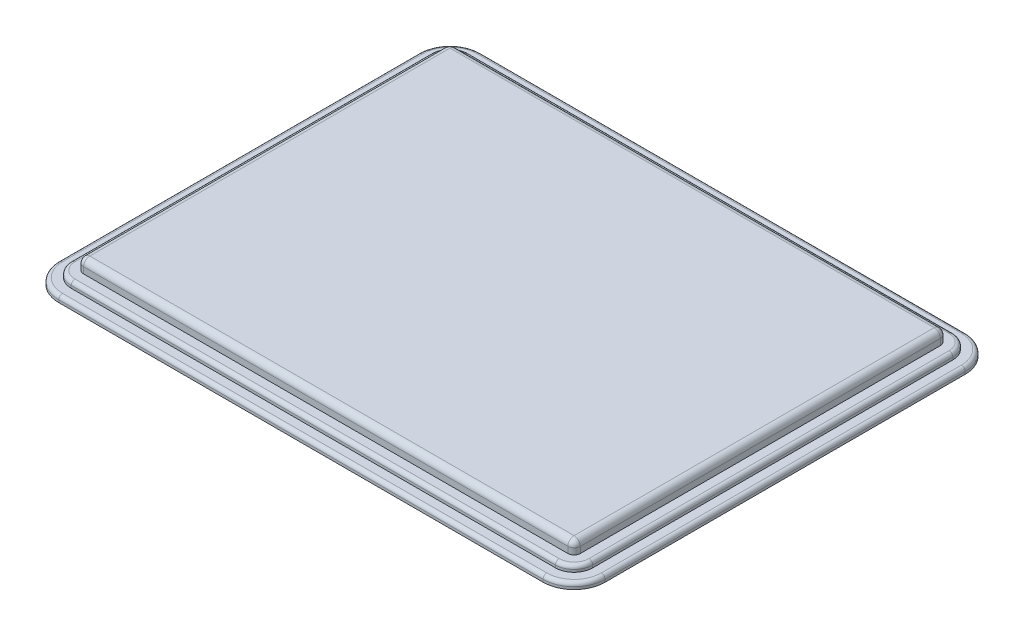
SolidWorks part; units mm, degrees
ref_plane "Front Plane" through (0, 0, 0) normal (0, 0, 1) x (1, 0, 0)
ref_plane "Top Plane" through (0, 0, 0) normal (0, 1, 0) x (1, 0, 0)
ref_plane "Right Plane" through (0, 0, 0) normal (1, 0, 0) x (0, 0, -1)
sketch "Sketch3" plane through (0, 0, 0) normal (0, 1, 0) x (1, 0, 0)
  line L1 (195, -150) -> (-195, -150)
  line L2 (200, -145) -> (200, 145)
  line L3 (195, 150) -> (-195, 150)
  line L4 (-200, -145) -> (-200, 145)
  line L5 (200, -150) -> (-200, 150) construction
  line L6 (200, 150) -> (-200, -150) construction
  arc A0 (-195, -150) -> (-200, -145) centre (-195, -145) cw
  arc A1 (200, 145) -> (195, 150) centre (195, 145) ccw
  arc A2 (195, -150) -> (200, -145) centre (195, -145) ccw
  arc A3 (-195, 150) -> (-200, 145) centre (-195, 145) ccw
  point P0 (0, 0)
  dimension "D3" = 5
  dimension "D1" = 400
  dimension "D2" = 300
extrude "Boss-Extrude1" add sketch "Sketch3" along normal blind 10
fillet "Fillet1" radius 5 8 edges at (-200, 10, 0) (-198.5355, 10, -148.5355) (0, 10, -150) (198.5355, 10, -148.5355) (200, 10, 0) (198.5355, 10, 148.5355) (0, 10, 150) (-198.5355, 10, 148.5355)
sketch "Sketch4" plane through (0, 0, 0) normal (0, -1, 0) x (1, 0, 0)
  line L0 (-210, 145) -> (-210, -145)
  line L1 (-195, -160) -> (195, -160)
  line L2 (210, -145) -> (210, 145)
  line L3 (195, 160) -> (-195, 160)
  line L4 (-200, 145) -> (-200, -145)
  line L5 (-195, -150) -> (195, -150)
  line L6 (200, -145) -> (200, 145)
  line L7 (195, 150) -> (-195, 150)
  line L8 (-200, 145) -> (-200, -145)
  line L9 (-195, -150) -> (195, -150)
  line L10 (200, -145) -> (200, 145)
  line L11 (195, 150) -> (-195, 150)
  arc A0 (-210, -145) -> (-195, -160) centre (-195, -145) ccw
  arc A1 (195, -160) -> (210, -145) centre (195, -145) ccw
  arc A2 (210, 145) -> (195, 160) centre (195, 145) ccw
  arc A3 (-195, 160) -> (-210, 145) centre (-195, 145) ccw
  arc A4 (-195, 150) -> (-200, 145) centre (-195, 145) ccw
  arc A5 (-200, -145) -> (-195, -150) centre (-195, -145) ccw
  arc A6 (195, -150) -> (200, -145) centre (195, -145) ccw
  arc A7 (200, 145) -> (195, 150) centre (195, 145) ccw
  arc A8 (-195, 150) -> (-200, 145) centre (-195, 145) ccw
  arc A9 (-200, -145) -> (-195, -150) centre (-195, -145) ccw
  arc A10 (195, -150) -> (200, -145) centre (195, -145) ccw
  arc A11 (200, 145) -> (195, 150) centre (195, 145) ccw
  arc M17 (-195, 150) -> (-200, 145) centre (-195, 145) ccw
  line M18 (-200, 145) -> (-200, -145)
  arc M19 (-200, -145) -> (-195, -150) centre (-195, -145) ccw
  line M20 (-195, -150) -> (195, -150)
  arc M21 (195, -150) -> (200, -145) centre (195, -145) ccw
  line M22 (200, -145) -> (200, 145)
  arc M23 (200, 145) -> (195, 150) centre (195, 145) ccw
  line M24 (195, 150) -> (-195, 150)
  dimension "D1" = 0
  dimension "D2" = 10
extrude "Boss-Extrude2" add sketch "Sketch4" along normal blind 5 separate body contours M24 M17 M18 M19 M20 M21 M22 M23 | L3 A3 L0 A0 L1 A1 L2 A2 M17 M24 M23 M22 M21 M20 M19 M18 | A8 L8 A9 L9 A10 L10 A11 L11
sketch "Sketch5" plane through (0, -5, 0) normal (0, -1, 0) x (1, 0, 0)
  line L0 (-220, 145) -> (-220, -145)
  line L1 (-195, -170) -> (195, -170)
  line L2 (220, -145) -> (220, 145)
  line L3 (195, 170) -> (-195, 170)
  line L4 (195, 160) -> (-195, 160)
  line L5 (-210, 145) -> (-210, -145)
  line L6 (-195, -160) -> (195, -160)
  line L7 (210, -145) -> (210, 145)
  line L8 (195, 160) -> (-195, 160)
  line L9 (-210, 145) -> (-210, -145)
  line L10 (-195, -160) -> (195, -160)
  line L11 (210, -145) -> (210, 145)
  arc A0 (-220, -145) -> (-195, -170) centre (-195, -145) ccw
  arc A1 (195, -170) -> (220, -145) centre (195, -145) ccw
  arc A2 (220, 145) -> (195, 170) centre (195, 145) ccw
  arc A3 (-195, 170) -> (-220, 145) centre (-195, 145) ccw
  arc A4 (-195, 160) -> (-210, 145) centre (-195, 145) ccw
  arc A5 (-210, -145) -> (-195, -160) centre (-195, -145) ccw
  arc A6 (195, -160) -> (210, -145) centre (195, -145) ccw
  arc A7 (210, 145) -> (195, 160) centre (195, 145) ccw
  arc A8 (-195, 160) -> (-210, 145) centre (-195, 145) ccw
  arc A9 (-210, -145) -> (-195, -160) centre (-195, -145) ccw
  arc A10 (195, -160) -> (210, -145) centre (195, -145) ccw
  arc A11 (210, 145) -> (195, 160) centre (195, 145) ccw
  line M17 (195, 160) -> (-195, 160)
  arc M18 (-195, 160) -> (-210, 145) centre (-195, 145) ccw
  line M19 (-210, 145) -> (-210, -145)
  arc M20 (-210, -145) -> (-195, -160) centre (-195, -145) ccw
  line M21 (-195, -160) -> (195, -160)
  arc M22 (195, -160) -> (210, -145) centre (195, -145) ccw
  line M23 (210, -145) -> (210, 145)
  arc M24 (210, 145) -> (195, 160) centre (195, 145) ccw
  dimension "D1" = 0
  dimension "D2" = 10
extrude "Boss-Extrude3" add sketch "Sketch5" along normal blind 5 separate body contours M24 M17 M18 M19 M20 M21 M22 M23 | L3 A3 L0 A0 L1 A1 L2 A2 M17 M24 M23 M22 M21 M20 M19 M18 | L8 A8 L9 A9 L10 A10 L11 A11
fillet "Fillet2" radius 3 8 edges at (-205.6066, 0, -155.6066) (-210, 0, 0) (-205.6066, 0, 155.6066) (0, 0, 160) (205.6066, 0, 155.6066) (210, 0, 0) (205.6066, 0, -155.6066) (0, 0, -160)
fillet "Fillet3" radius 3 8 edges at (-212.6777, -5, -162.6777) (-220, -5, 0) (-212.6777, -5, 162.6777) (0, -5, 170) (212.6777, -5, 162.6777) (220, -5, 0) (212.6777, -5, -162.6777) (0, -5, -170)
